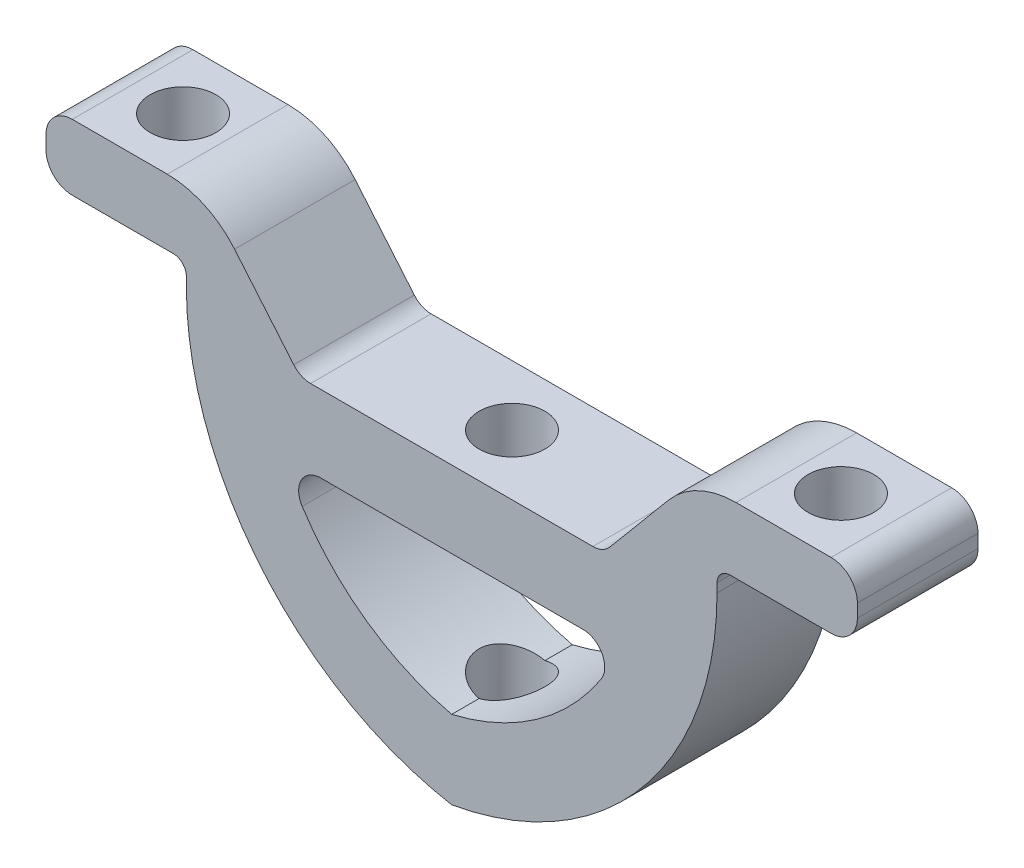
SolidWorks part; units mm, degrees
ref_plane "Front Plane" through (0, 0, 0) normal (0, 0, 1) x (1, 0, 0)
ref_plane "Top Plane" through (0, 0, 0) normal (0, 1, 0) x (1, 0, 0)
ref_plane "Right Plane" through (0, 0, 0) normal (1, 0, 0) x (0, 0, -1)
sketch "Sketch1" plane through (0, 0, 0) normal (0, 0, 1) x (1, 0, 0)
  line L0 (-8.65, 0) -> (-6.4826, 0)
  line L1 (-4.9505, -0.7144) -> (-3.6021, -2.3214)
  line L2 (-3.2191, -2.5) -> (3.2191, -2.5)
  line L3 (0, -9.2101) -> (0, -2.5) construction
  line L4 (-9.25, -0.6) -> (-9.25, -0.9)
  line L5 (-8.65, -1.5) -> (-6.35, -1.5)
  line L6 (-6.05, -1.8) -> (-6.05, -2)
  line L7 (-6.05, -2) -> (0, -9.2101) construction
  line L8 (-7.5, -1.5) -> (-7.5, 0) construction
  line L9 (-7.5, 0) -> (0, 0) construction
  line L10 (0, 0) -> (0, -2.5) construction
  line L11 (-8.3, 0) -> (-7.5, -1.5) construction
  line L12 (-7.5, -1.5) -> (-6.7, 0) construction
  line L13 (9.25, -0.6) -> (9.25, -0.9)
  line L14 (6.05, -1.8) -> (6.05, -2)
  line L15 (8.65, -1.5) -> (6.35, -1.5)
  line L16 (8.65, 0) -> (6.4826, 0)
  line L17 (4.9505, -0.7144) -> (3.6021, -2.3214)
  line L18 (2.9896, -4.25) -> (-2.9896, -4.25)
  arc A0 (-6.05, -2) -> (0, -9.2101) centre (1.2713, -2) ccw
  arc A1 (6.05, -2) -> (0, -9.2101) centre (-1.2713, -2) cw
  arc A2 (-3.4097, -5.0211) -> (0, -7.4243) centre (1.2713, -2) ccw
  arc A3 (3.6021, -2.3214) -> (3.2191, -2.5) centre (3.2191, -2) cw
  arc A4 (-3.2191, -2.5) -> (-3.6021, -2.3214) centre (-3.2191, -2) cw
  arc A5 (-2.9896, -4.25) -> (-3.4097, -5.0211) centre (-2.9896, -4.75) ccw
  arc A6 (3.4097, -5.0211) -> (0, -7.4243) centre (-1.2713, -2) cw
  arc A7 (2.9896, -4.25) -> (3.4097, -5.0211) centre (2.9896, -4.75) cw
  arc A8 (6.4826, 0) -> (4.9505, -0.7144) centre (6.4826, -2) ccw
  arc A9 (-4.9505, -0.7144) -> (-6.4826, 0) centre (-6.4826, -2) ccw
  arc A10 (6.35, -1.5) -> (6.05, -1.8) centre (6.35, -1.8) ccw
  arc A11 (-6.05, -1.8) -> (-6.35, -1.5) centre (-6.35, -1.8) ccw
  arc A12 (9.25, -0.9) -> (8.65, -1.5) centre (8.65, -0.9) cw
  arc A13 (-8.65, -1.5) -> (-9.25, -0.9) centre (-8.65, -0.9) cw
  arc A14 (-9.25, -0.6) -> (-8.65, 0) centre (-8.65, -0.6) cw
  arc A15 (9.25, -0.6) -> (8.65, 0) centre (8.65, -0.6) ccw
  point P28 (3.4523, -2.5)
  point P31 (-3.4523, -2.5)
  point P37 (0, -4.25)
  point P39 (5.55, 0)
  point P42 (-5.55, 0)
  point P45 (6.05, -1.5)
  point P48 (-6.05, -1.5)
  point P51 (9.25, -1.5)
  point P54 (-9.25, -1.5)
  point P57 (-9.25, 0)
  point P60 (9.25, 0)
  dimension "D1" = 7.5
  dimension "D2" = 1.6
  dimension "D9" = 1.75
  dimension "D11" = 0.5
  dimension "D12" = 2
  dimension "D13" = 0.3
  dimension "D14" = 0.6
  dimension "D15" = 0.6
  dimension "D3" = 1.75
  dimension "D4" = 1.5
  dimension "D5" = 0.5
  dimension "D6" = 0.5
  dimension "D7" = 2.5
  dimension "D8" = 50
  dimension "D10" = 1.75
extrude "Boss-Extrude1" add sketch "Sketch1" along normal mid plane 2.75
sketch "Sketch2" plane through (0, 0, 0) normal (0, 1, 0) x (1, 0, 0)
  line L0 (-7.5, 0) -> (0, 0) construction
  line L1 (0, 0) -> (7.5, 0) construction
  circle A0 centre (0, 0) radius 0.75
  circle A1 centre (-7.5, 0) radius 0.75
  circle A2 centre (7.5, 0) radius 0.75
  dimension "D1" = 1.5
extrude "Cut-Extrude1" cut sketch "Sketch2" against normal through all both and the other way through all
